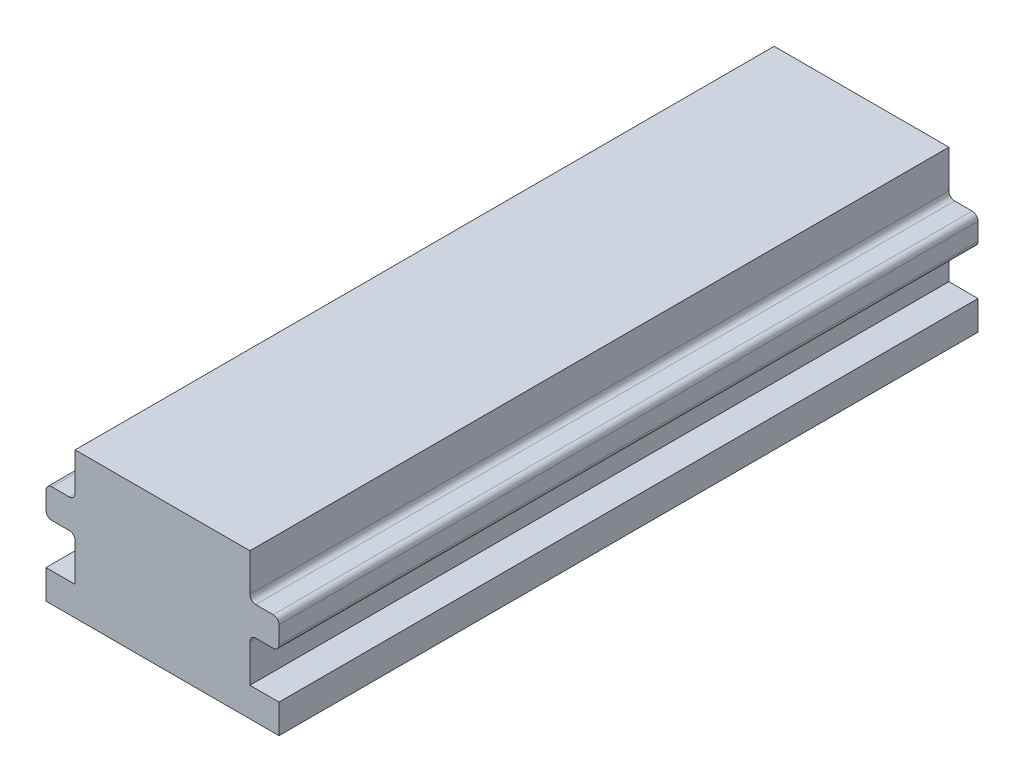
SolidWorks part; units mm, degrees
ref_plane "Plane1" through (0, 0, 0) normal (0, 0, 1) x (1, 0, 0)
ref_plane "Plane2" through (0, 0, 0) normal (0, 1, 0) x (1, 0, 0)
ref_plane "Plane3" through (0, 0, 0) normal (1, 0, 0) x (0, 0, -1)
sketch "Sketch1" plane through (0, 0, 0) normal (0, 0, 1) x (1, 0, 0)
  line L1 (0, 0) -> (50.8, 0)
  line L2 (0, 0) -> (0, 31.75)
  line L3 (0, 31.75) -> (50.8, 31.75)
  line L4 (50.8, 0) -> (50.8, 31.75)
  dimension "D1" = 31.75
  dimension "D2" = 50.8
extrude "Base-Extrude" add sketch "Sketch1" along normal blind 152.4
sketch "Sketch2" plane through (0, 0, 152.4) normal (0, 0, 1) x (1, 0, 0)
  line L0 (50.8, 6.35) -> (44.45, 6.35)
  line L1 (50.8, 0) -> (50.8, 31.75) construction
  line L2 (0, 31.75) -> (0, 0) construction
  line L3 (49.53, 15.875) -> (45.72, 15.875)
  line L4 (49.53, 22.225) -> (45.72, 22.225)
  line L5 (44.45, 36.83) -> (44.45, 23.495)
  line L6 (6.35, 38.1) -> (6.35, 23.495)
  line L7 (0, 0) -> (50.8, 0) construction
  line L8 (6.35, 6.35) -> (0, 6.35)
  line L9 (5.08, 15.875) -> (1.27, 15.875)
  line L10 (5.08, 22.225) -> (1.27, 22.225)
  line L11 (44.45, 14.605) -> (44.45, 6.35)
  line L12 (6.35, 14.605) -> (6.35, 6.35)
  line L13 (50.8, 20.955) -> (50.8, 17.145)
  line L14 (0, 20.955) -> (0, 17.145)
  line L15 (0, 6.35) -> (-3.81, 6.35)
  line L16 (-3.81, 6.35) -> (-3.81, 38.1)
  line L17 (-3.81, 38.1) -> (6.35, 38.1)
  line L18 (44.45, 36.83) -> (54.61, 36.83)
  line L19 (54.61, 36.83) -> (54.61, 6.35)
  line L20 (54.61, 6.35) -> (50.8, 6.35)
  arc A0 (5.08, 15.875) -> (6.35, 14.605) centre (5.08, 14.605) cw
  arc A1 (0, 17.145) -> (1.27, 15.875) centre (1.27, 17.145) ccw
  arc A2 (1.27, 22.225) -> (0, 20.955) centre (1.27, 20.955) ccw
  arc A3 (6.35, 23.495) -> (5.08, 22.225) centre (5.08, 23.495) cw
  arc A4 (45.72, 22.225) -> (44.45, 23.495) centre (45.72, 23.495) cw
  arc A5 (50.8, 20.955) -> (49.53, 22.225) centre (49.53, 20.955) ccw
  arc A6 (49.53, 15.875) -> (50.8, 17.145) centre (49.53, 17.145) ccw
  arc A7 (44.45, 14.605) -> (45.72, 15.875) centre (45.72, 14.605) cw
  point P26 (6.35, 15.875)
  point P31 (0, 22.225)
  point P38 (50.8, 22.225)
  point P41 (50.8, 15.875)
  point P44 (44.45, 15.875)
  dimension "D6" = 1.27
  dimension "D1" = 6.35
  dimension "D2" = 6.35
  dimension "D3" = 6.35
  dimension "D4" = 9.525
  dimension "D5" = 6.35
extrude "Cut-Extrude1" cut sketch "Sketch2" against normal blind 152.4
